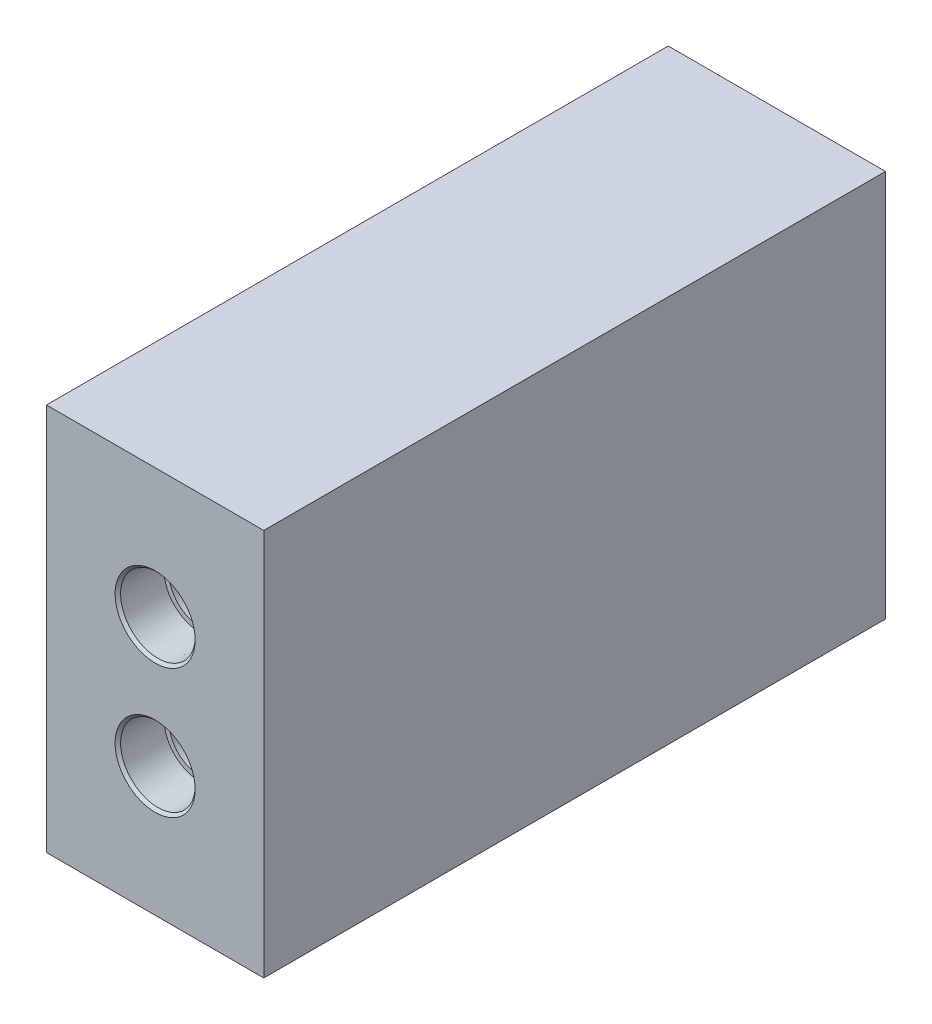
SolidWorks part; units mm, degrees
material "6061 Alloy"
ref_plane "Front Plane" through (0, 0, 0) normal (0, 0, 1) x (1, 0, 0)
ref_plane "Top Plane" through (0, 0, 0) normal (0, 1, 0) x (1, 0, 0)
ref_plane "Right Plane" through (0, 0, 0) normal (1, 0, 0) x (0, 0, -1)
sketch "block_sketch" plane through (0, 0, 0) normal (1, 0, 0) x (0, 0, -1)
  line L1 (71.5393, 44.5969) -> (-71.5393, 44.5969)
  line L2 (71.5393, 44.5969) -> (71.5393, -44.5969)
  line L3 (71.5393, -44.5969) -> (-71.5393, -44.5969)
  line L4 (-71.5393, 44.5969) -> (-71.5393, -44.5969)
  line L5 (71.5393, 44.5969) -> (-71.5393, -44.5969) construction
  line L6 (71.5393, -44.5969) -> (-71.5393, 44.5969) construction
  point P0 (0, 0)
extrude "block" add sketch "block_sketch" along normal mid plane 50
hole_wizard "1/8 NPT_pressure_sensor_connector" positions "Sketch3" profile "Sketch4" size "1/8" standard "ANSI Inch"
sketch "Sketch3" plane through (-25, 14.5969, 0) normal (1, 0, 0) x (0, -1, 0)
  line L8 (59.1938, -71.5393) -> (59.1938, 71.5393) construction
  line L9 (-30, 71.5393) -> (-30, -71.5393) construction
  line L11 (-0.2687, 71.5393) -> (-0.2687, -71.5393) construction
  line L12 (59.1938, 71.5393) -> (-30, 71.5393) construction
  line L14 (29.4626, 71.5393) -> (29.4626, -71.5393) construction
  line L15 (-30, -71.5393) -> (59.1938, -71.5393) construction
  line L17 (59.1938, 0) -> (29.4626, 0) construction
  line L18 (29.4626, 0) -> (-0.2687, 0) construction
  line L19 (-0.2687, 0) -> (-30, 0) construction
  point P0 (29.4626, -38.5526)
  point P13 (29.4626, 38.5526)
  point P64 (59.1938, 0)
  point P69 (-0.2687, 38.5526)
  point P71 (-0.2687, -38.5526)
  point P74 (-0.2687, -44.0113)
  point P75 (0, 0)
  point P76 (0, 0)
  point P77 (29.4626, 38.5526)
sketch "Sketch4" plane through (-25, -14.8656, 38.5526) normal (0, 1, 0) x (0, 0, 1)
  line L0 (0, 0) -> (0, 14.1535)
  line L1 (4.2164, 11.62) -> (0, 14.1535)
  line L2 (-4.2164, 11.62) -> (0, 14.1535) construction
  line L3 (4.2164, 11.62) -> (4.2164, 6.92)
  line L4 (4.2164, 6.92) -> (4.9552, 6.92)
  line L5 (4.9552, 6.92) -> (5.1434, 0.635)
  line L6 (5.1434, 0.635) -> (5.7784, 0)
  line L7 (5.7784, 0) -> (0, 0)
  line L8 (0, -6.35) -> (0, 107.95) construction
  line L9 (-5.1434, 0.635) -> (-5.7784, 0) construction
  line L11 (-4.2164, 6.92) -> (-4.9552, 6.92) construction
  line L12 (-4.9552, 6.92) -> (-5.1434, 0.635) construction
  dimension "Tap Drill Dia." = 8.4328
  dimension "Tap Drill Depth" = 11.62
  dimension "Thread Dia." = 10.2867
  dimension "Thread Angle" = 3.43
  dimension "Thread Depth" = 6.92
  dimension "C'Sink Dia." = 11.5567
  dimension "C'Sink Angle" = 90
  dimension "Drill Angle" = 118
hole_wizard "3/8 NPT_flow_connector" positions "Sketch5" profile "Sketch6" size "3/8" standard "ANSI Inch"
sketch "Sketch5" plane through (0, 0, 71.5393) normal (0, 0, 1) x (1, 0, 0)
  line L3 (-25, 0) -> (25, 0) construction
  line L4 (-25, 44.5969) -> (-25, -44.5969) construction
  line L5 (25, 44.5969) -> (25, -44.5969) construction
  line L6 (0, -44.5969) -> (0, -14.8656) construction
  line L7 (25, -44.5969) -> (-25, -44.5969) construction
  line L8 (0, -14.8656) -> (0, 14.8656) construction
  line L9 (0, 14.8656) -> (0, 44.5969) construction
  line L10 (25, 44.5969) -> (-25, 44.5969) construction
  point P8 (0, 14.8656)
  point P10 (0, -14.8656)
  point P37 (0, 0)
  point P38 (0, 0)
  point P39 (13.47, -20.7721)
sketch "Sketch6" plane through (0, 14.8656, 71.5393) normal (1, 0, 0) x (0, -1, 0)
  line L0 (0, 0) -> (0, 21.6686)
  line L1 (7.1374, 17.38) -> (0, 21.6686)
  line L2 (-7.1374, 17.38) -> (0, 21.6686) construction
  line L3 (7.1374, 17.38) -> (7.1374, 10.33)
  line L4 (7.1374, 10.33) -> (8.2822, 10.33)
  line L5 (8.2822, 10.33) -> (8.5725, 0.635)
  line L6 (8.5725, 0.635) -> (9.2075, 0)
  line L7 (9.2075, 0) -> (0, 0)
  line L8 (0, -6.35) -> (0, 107.95) construction
  line L9 (-8.5725, 0.635) -> (-9.2075, 0) construction
  line L11 (-7.1374, 10.33) -> (-8.2822, 10.33) construction
  line L12 (-8.2822, 10.33) -> (-8.5725, 0.635) construction
  dimension "Tap Drill Dia." = 14.2748
  dimension "Tap Drill Depth" = 17.38
  dimension "Thread Dia." = 17.145
  dimension "Thread Angle" = 3.43
  dimension "Thread Depth" = 10.33
  dimension "C'Sink Dia." = 18.415
  dimension "C'Sink Angle" = 90
  dimension "Drill Angle" = 118
hole_wizard "flow_channel" positions "Sketch14" profile "Sketch15" hole size "1/2" standard "ANSI Inch"
sketch "Sketch14" plane through (0, 0, 71.5393) normal (0, 0, 1) x (1, 0, 0)
  point P0 (0, 14.8656)
  point P3 (0, -14.8656)
sketch "Sketch15" plane through (0, 14.8656, 71.5393) normal (1, 0, 0) x (0, -1, 0)
  line L0 (0, 0) -> (0, 43.8155)
  line L1 (0, 43.8155) -> (6.35, 40)
  line L2 (6.35, 40) -> (6.35, 0)
  line L5 (6.35, 0) -> (0, 0)
  line L10 (0, 43.8155) -> (-6.35, 40) construction
  line L11 (0, -6.35) -> (0, 107.95) construction
  dimension "Hole Dia." = 12.7
  dimension "Hole Depth" = 40
  dimension "Drill Angle" = 118
mirror "flow_mirror" about plane through (0, 0, 0) normal (0, 0, 1) of "flow_channel", "3/8 NPT_flow_connector"
sketch "Sketch11" plane through (-25, 14.5969, 0) normal (1, 0, 0) x (0, -1, 0)
  circle A0 centre (29.4626, 38.5526) radius 1.6
  circle A1 centre (29.4626, -38.5526) radius 1.6
  circle A2 centre (-0.2687, 38.5526) radius 1.6
  circle A3 centre (-0.2687, -38.5526) radius 1.6
  dimension "D1" = 3.2
extrude "pressure_sensor_hole" cut sketch "Sketch11" along normal up to next
hole_wizard "M8x1.0 Tapped Hole1" positions "Sketch9" profile "Sketch10" tap size "M8x1.0" standard "ANSI Metric" end condition through all
sketch "Sketch9" plane through (0, 0, 71.5393) normal (0, 0, 1) x (1, 0, 0)
  point P3 (0, -14.8656)
  point P8 (0, 0)
cosmetic thread "Hole Thread1" parameters "D2"=8
sketch "Sketch10" plane through (0, -14.8656, 71.5393) normal (1, 0, 0) x (0, -1, 0)
  line L0 (0, 0) -> (0, 143.0786)
  line L1 (0, 143.0786) -> (3.5, 143.0786)
  line L2 (3.5, 143.0786) -> (3.5, 0)
  line L5 (3.5, 0) -> (0, 0)
  line L11 (0, -6.35) -> (0, 107.95) construction
  dimension "Thru Tap Drill Dia." = 7
  dimension "Thru Tap Drill Depth" = 143.0786
hole_wizard "M10x1.0 Tapped Hole1" positions "Sketch12" profile "Sketch13" tap size "M10x1.0" standard "ANSI Metric" end condition through all
sketch "Sketch12" plane through (0, 0, 71.5393) normal (0, 0, 1) x (1, 0, 0)
  point P0 (0, 14.8656)
sketch "Sketch13" plane through (0, 14.8656, 71.5393) normal (1, 0, 0) x (0, -1, 0)
  line L0 (0, 0) -> (0, 143.0786)
  line L1 (0, 143.0786) -> (4.5, 143.0786)
  line L2 (4.5, 143.0786) -> (4.5, 0)
  line L5 (4.5, 0) -> (0, 0)
  line L11 (0, -6.35) -> (0, 107.95) construction
  dimension "Thru Tap Drill Dia." = 9
  dimension "Thru Tap Drill Depth" = 143.0786
cosmetic thread "Hole Thread3" parameters "D2"=10
equation "\"pressure_hole_diameter\"=3.2"
equation "\"D1@Sketch11\"=\"pressure_hole_diameter\""
